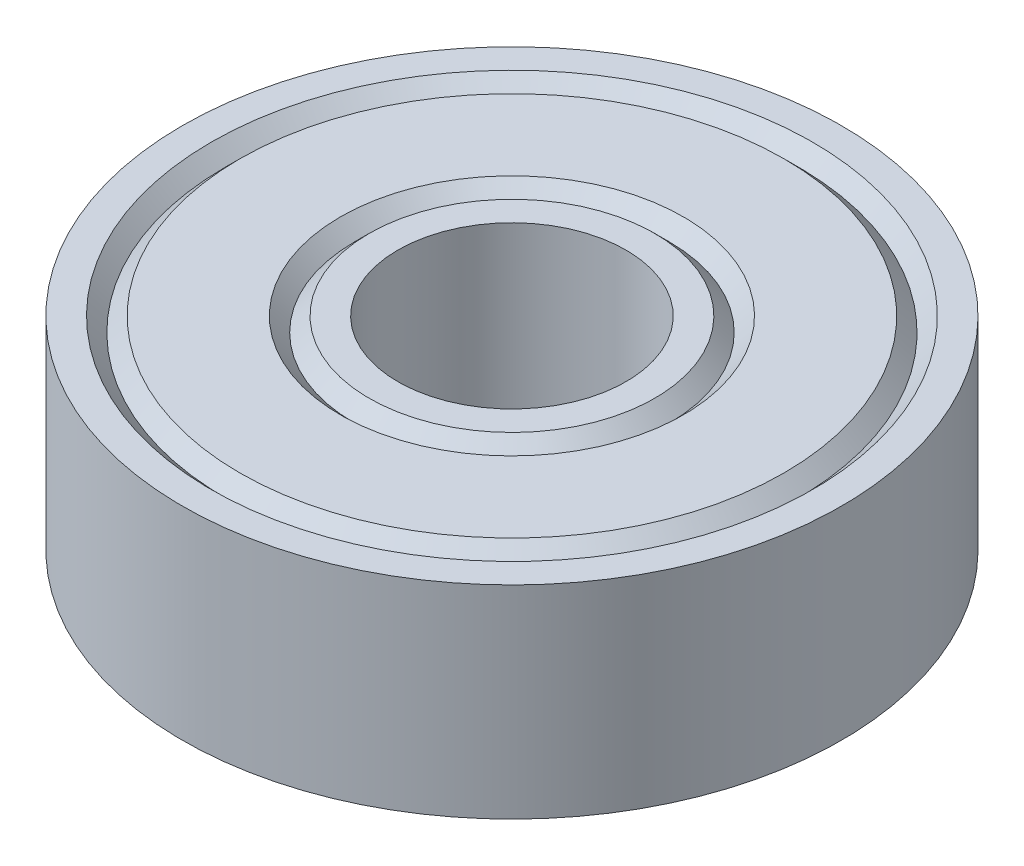
SolidWorks part; units mm, degrees
ref_plane "Front Plane" through (0, 0, 0) normal (0, 0, 1) x (1, 0, 0)
ref_plane "Top Plane" through (0, 0, 0) normal (0, 1, 0) x (1, 0, 0)
ref_plane "Right Plane" through (0, 0, 0) normal (1, 0, 0) x (0, 0, -1)
sketch "Sketch1" plane through (0, 0, 0) normal (0, 0, 1) x (1, 0, 0)
  line L0 (0, 4) -> (0, -4) construction
  line L1 (-4.5, 4) -> (-5.6333, 4)
  line L2 (-4.5, 4) -> (-4.5, -4)
  line L3 (-4.5, -4) -> (-5.6333, -4)
  line L4 (-13, 4) -> (-13, -4)
  line L5 (-11.8667, 4) -> (-11.3, 3.4333)
  line L6 (-11.3, 3.4333) -> (-10.7333, 4)
  line L7 (-6.7667, 4) -> (-6.2, 3.4333)
  line L8 (-6.2, 3.4333) -> (-5.6333, 4)
  line L9 (-11.8667, -4) -> (-11.3, -3.4333)
  line L10 (-11.3, -3.4333) -> (-10.7333, -4)
  line L11 (-6.7667, -4) -> (-6.2, -3.4333)
  line L12 (-6.2, -3.4333) -> (-5.6333, -4)
  line L13 (-6.7667, -4) -> (-10.7333, -4)
  line L14 (-11.8667, -4) -> (-13, -4)
  line L15 (-11.8667, 4) -> (-13, 4)
  line L16 (-6.7667, 4) -> (-10.7333, 4)
  line L17 (-11.3, 3.4333) -> (-6.2, 3.4333) construction
  line L18 (-11.3, 3.4333) -> (-11.3, -3.4333) construction
  line L19 (-6.2, -3.4333) -> (-11.3, -3.4333) construction
  line L20 (-6.2, 3.4333) -> (-6.2, -3.4333) construction
  line L21 (-11.3, 0) -> (-9.6, 0) construction
  line L22 (-5.6333, 4) -> (-6.7667, 4) construction
  line L23 (-9.6, 0) -> (-7.9, 0) construction
  line L24 (-11.3, 0) -> (-13, 0) construction
  line L25 (-7.9, 0) -> (-6.2, 0) construction
  line L26 (-6.2, 0) -> (-4.5, 0) construction
  dimension "D1" = 8
  dimension "D2" = 9
  dimension "D3" = 26
revolve "Revolve1" add sketch "Sketch1" angle 360 about L0
